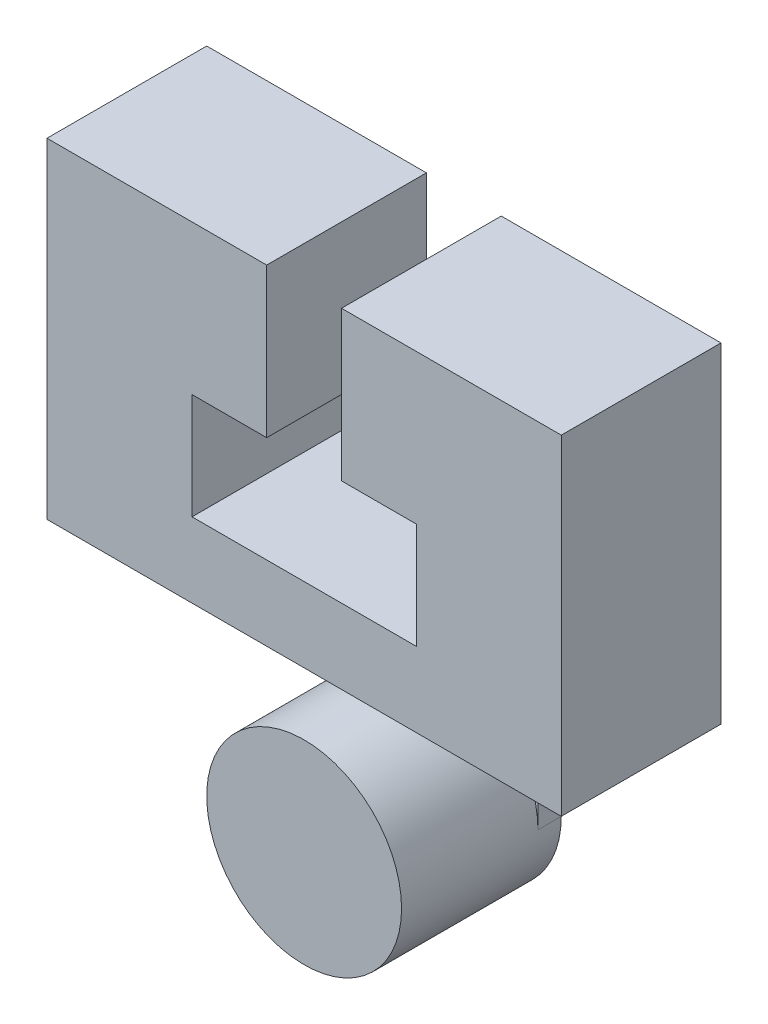
SolidWorks part; units mm, degrees
material "ASTM A36 Steel"
ref_plane "Front Plane" through (0, 0, 0) normal (0, 0, 1) x (1, 0, 0)
ref_plane "Top Plane" through (0, 0, 0) normal (0, 1, 0) x (1, 0, 0)
ref_plane "Right Plane" through (0, 0, 0) normal (1, 0, 0) x (0, 0, -1)
sketch "Sketch1" plane through (0, 0, 0) normal (0, 0, 1) x (1, 0, 0)
  circle A0 centre (0, 0) radius 15.494
  dimension "D1" = 30.988
extrude "Boss-Extrude1" add sketch "Sketch1" against normal blind 25.4
sketch "Sketch2" plane through (0, 0, -25.4) normal (0, 0, -1) x (-1, 0, 0)
  line L1 (-15.494, 0) -> (-15.494, 25.4)
  line L2 (-15.494, 25.4) -> (15.494, 25.4)
  line L3 (15.494, 25.4) -> (15.494, 0)
  circle A0 centre (0, 0) radius 15.494 construction
  arc A1 (15.494, 0) -> (-15.494, 0) centre (0, 0) ccw
  dimension "D1" = 25.4
  dimension "D2" = 30.988
extrude "Boss-Extrude2" add sketch "Sketch2" against normal blind 3.7084
sketch "Sketch3" plane through (0, 0, -25.4) normal (0, 0, -1) x (-1, 0, 0)
  line L0 (-15.494, 25.4) -> (-40.894, 25.4)
  line L1 (-40.894, 25.4) -> (-40.894, 77.9018)
  line L2 (-40.894, 77.9018) -> (40.894, 77.9018)
  line L3 (40.894, 77.9018) -> (40.894, 25.4)
  line L4 (40.894, 25.4) -> (15.494, 25.4)
  line L5 (15.494, 25.4) -> (-15.494, 25.4) construction
  line L6 (-15.494, 25.4) -> (15.494, 25.4)
  dimension "D1" = 25.4
  dimension "D2" = 25.4
  dimension "D3" = 52.5018
extrude "Boss-Extrude4" add sketch "Sketch3" against normal up to surface (25.4 mm away) up to face at (15.494, 0, 0)
sketch "Sketch4" plane through (0, 0, -25.4) normal (0, 0, -1) x (-1, 0, 0)
  line L0 (-5.9448, 77.9018) -> (-5.9448, 54.1274)
  line L1 (40.894, 77.9018) -> (-40.894, 77.9018) construction
  line L2 (-5.9448, 54.1274) -> (-17.8308, 54.1274)
  line L3 (-17.8308, 54.1274) -> (-17.8308, 37.2872)
  line L4 (-17.8308, 37.2872) -> (17.8308, 37.2872)
  line L5 (17.8308, 37.2872) -> (17.8308, 54.1274)
  line L6 (17.8308, 54.1274) -> (5.9555, 54.1274)
  line L7 (5.9555, 54.1274) -> (5.9555, 77.9018)
  line L8 (5.9555, 77.9018) -> (-5.9448, 77.9018)
  line L9 (-40.894, 25.4) -> (-15.494, 25.4) construction
  point P14 (0, 37.2872)
  dimension "D1" = 16.8402
  dimension "D2" = 11.8872
  dimension "D3" = 35.6616
  dimension "D4" = 11.886
  dimension "D5" = 11.8753
extrude "Cut-Extrude1" cut sketch "Sketch4" against normal through all
equation "\"L\"= 1'Length"
equation "\"A\"= 1.22'A Diameter"
equation "\"B\"= 0.146'Thickness/Height"
equation "\"C\"= 0.468'Thickness/Height"
equation "\"D\"= 0.663'Thickness/Height"
equation "\"E\"= 0.936'Thickness/Height"
equation "\"D1@Sketch1\"=\"A\""
equation "\"D1@Boss-Extrude1\"=\"L\""
equation "\"D1@Sketch2\"=\"L\""
equation "\"D2@Sketch2\"=\"A\""
equation "\"D1@Boss-Extrude2\"=\"B\""
equation "\"D1@Sketch3\"=\"L\""
equation "\"D2@Sketch3\"=\"L\""
equation "\"D3@Sketch3\"=\"C\"+\"D\"+\"E\""
equation "\"D1@Sketch4\"=\"D\""
equation "\"D2@Sketch4\"=\"C\""
equation "\"BC\"= \"C\" * 3'C Length"
equation "\"D3@Sketch4\"=\"BC\""
equation "\"D4@Sketch4\"=\"BC\"*.3333"
equation "\"D5@Sketch4\"=\"BC\"*.333"
